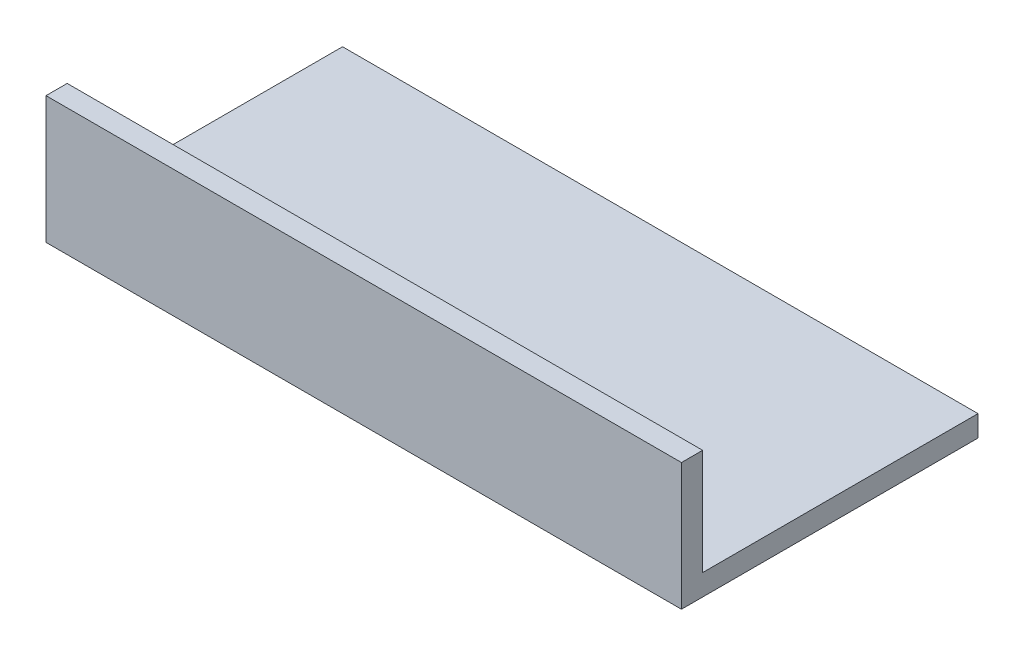
SolidWorks part; units mm, degrees
ref_plane "正面" through (0, 0, 0) normal (0, 0, 1) x (1, 0, 0)
ref_plane "平面" through (0, 0, 0) normal (0, 1, 0) x (1, 0, 0)
ref_plane "右側面" through (0, 0, 0) normal (1, 0, 0) x (0, 0, -1)
sketch "ｽｹｯﾁ1" plane through (0, 0, 0) normal (0, 0, 1) x (1, 0, 0)
  line L1 (-75, 12.5) -> (75, 12.5)
  line L2 (-75, 12.5) -> (-75, -12.5)
  line L3 (-75, -12.5) -> (75, -12.5)
  line L4 (75, 12.5) -> (75, -12.5)
  line L5 (-75, 12.5) -> (75, -12.5) construction
  line L6 (-75, -12.5) -> (75, 12.5) construction
  point P0 (0, 0)
  dimension "D1" = 25
  dimension "D2" = 150
extrude "ﾎﾞｽ - 押し出し1" add sketch "ｽｹｯﾁ1" along normal blind 5
sketch "ｽｹｯﾁ3" plane through (0, -12.5, 0) normal (0, -1, 0) x (1, 0, 0)
  line L0 (75, 5) -> (75, 0) construction
  line L1 (-75, 5) -> (75, 5)
  line L2 (-75, 5) -> (-75, -65)
  line L3 (-75, -65) -> (75, -65)
  line L4 (75, 5) -> (75, -65)
  dimension "D1" = 70
extrude "ﾎﾞｽ - 押し出し2" add sketch "ｽｹｯﾁ3" along normal blind 5
